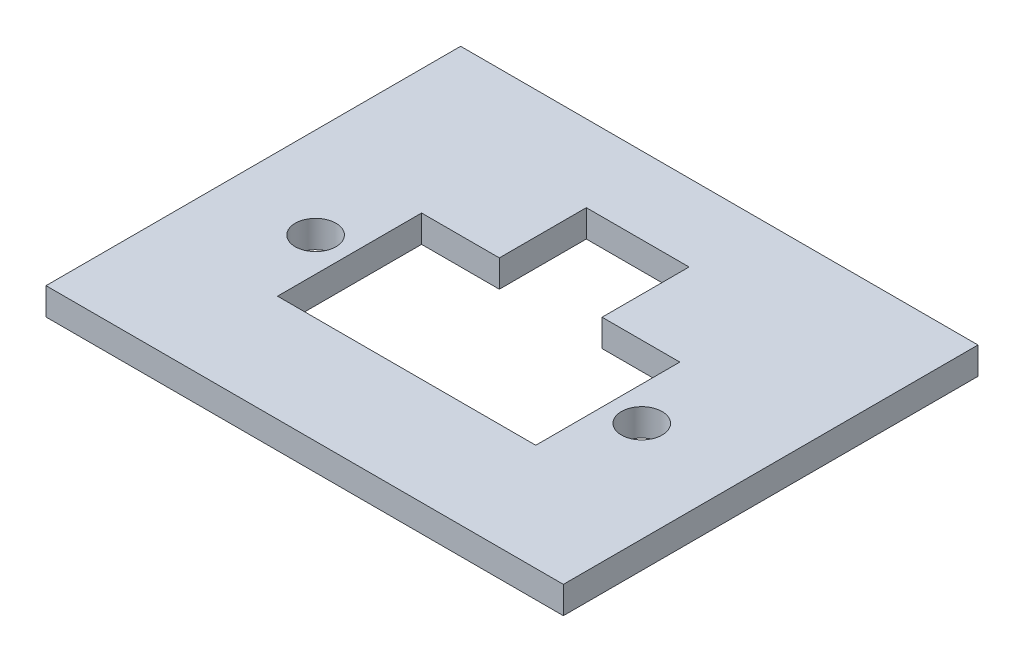
SolidWorks part; units mm, degrees
ref_plane "Front Plane" through (0, 0, 0) normal (0, 0, 1) x (1, 0, 0)
ref_plane "Top Plane" through (0, 0, 0) normal (0, 1, 0) x (1, 0, 0)
ref_plane "Right Plane" through (0, 0, 0) normal (1, 0, 0) x (0, 0, -1)
sketch "Sketch1" plane through (0, 0, 0) normal (0, 1, 0) x (1, 0, 0)
  line L25 (0, 0) -> (-19, 0)
  line L26 (-19, 0) -> (-19, 19)
  line L27 (-19, 19) -> (0, 19)
  line L28 (0, 19) -> (0, 0)
  line L29 (0, 0) -> (0, 7.875)
  line L30 (-19, 0) -> (-19, 7.875)
  line L32 (9.8789, 24.6604) -> (-28.1885, 24.6604)
  line L33 (9.8789, 24.6604) -> (9.8789, -5.8481)
  line L34 (0, 0) -> (0, 14.6)
  line L35 (0, 14.6) -> (-19, 14.6)
  line L36 (-9.5, 19) -> (-5.72, 19)
  line L37 (-5.72, 19) -> (-5.72, 14.6)
  line L38 (-9.5, 19) -> (-13.28, 19)
  line L39 (-13.28, 19) -> (-13.28, 14.6)
  line L40 (9.8789, -5.8481) -> (-28.1885, -5.8481)
  line L41 (-28.1885, 24.6604) -> (-28.1885, -5.8481)
  circle A2 centre (2.5, 7.875) radius 1.5
  circle A3 centre (-21.5, 7.875) radius 1.5
extrude "Boss-Extrude1" add sketch "Sketch1" along normal blind 2 contours L32 L41 L40 L33 A3 A2 L27 L28 L25 L26 | L39 L27 L26 L35 | L27 L37 L35 L28
sketch "Sketch2" plane through (0, 0, 0) normal (0, -1, 0) x (1, 0, 0)
  line L0 (0, -14.6) -> (0, 0) construction
  line L1 (-19, -14.6) -> (-13.28, -14.6)
  line L2 (-19, -14.6) -> (-19, -12.6)
  line L3 (-19, -12.6) -> (-13.28, -12.6)
  line L4 (-13.28, -14.6) -> (-13.28, -12.6)
  line L5 (-5.72, -14.6) -> (0, -14.6)
  line L6 (-5.72, -14.6) -> (-5.72, -12.6)
  line L7 (-5.72, -12.6) -> (0, -12.6)
  line L8 (0, -14.6) -> (0, -12.6)
  line L9 (-19, 0) -> (-19, -14.6) construction
  line L10 (0, 0) -> (-19, 0)
  line L11 (0, 0) -> (0, -2)
  line L12 (0, -2) -> (-19, -2)
  line L13 (-19, 0) -> (-19, -2)
extrude "Boss-Extrude2" add sketch "Sketch2" against normal up to surface (2 mm away) up to face at (-9.5, 2, -12.05)
sketch "Sketch4" plane through (0, 2, 0) normal (0, 1, 0) x (1, 0, 0)
  line L1 (-24.8108, 12.4008) -> (-19.5046, 12.4008)
  line L2 (-24.8108, 12.4008) -> (-24.8108, 4.993)
  line L3 (-24.8108, 4.993) -> (-19.5046, 4.993)
  line L4 (-19.5046, 12.4008) -> (-19.5046, 4.993)
  line L5 (0.7222, 11.2975) -> (5.1353, 11.2975)
  line L6 (0.7222, 11.2975) -> (0.7222, 5.3608)
  line L7 (0.7222, 5.3608) -> (5.1353, 5.3608)
  line L8 (5.1353, 11.2975) -> (5.1353, 5.3608)
extrude "Boss-Extrude3" add sketch "Sketch4" against normal up to surface (2 mm away) up to face at (-9.5, 0, -11.55)
sketch "Sketch5" plane through (0, 2, 0) normal (0, 1, 0) x (1, 0, 0)
  line L0 (-9.5, 2) -> (-9.5, 7.3)
  line L1 (-19, 2) -> (0, 2) construction
  line L2 (-9.5, 7.3) -> (-21.5, 7.3)
  line L3 (-21.5, 7.3) -> (2.5, 7.3)
  circle A0 centre (-21.5, 7.3) radius 1.5
  circle A1 centre (2.5, 7.3) radius 1.5
extrude "Cut-Extrude1" cut sketch "Sketch5" against normal blind 10
